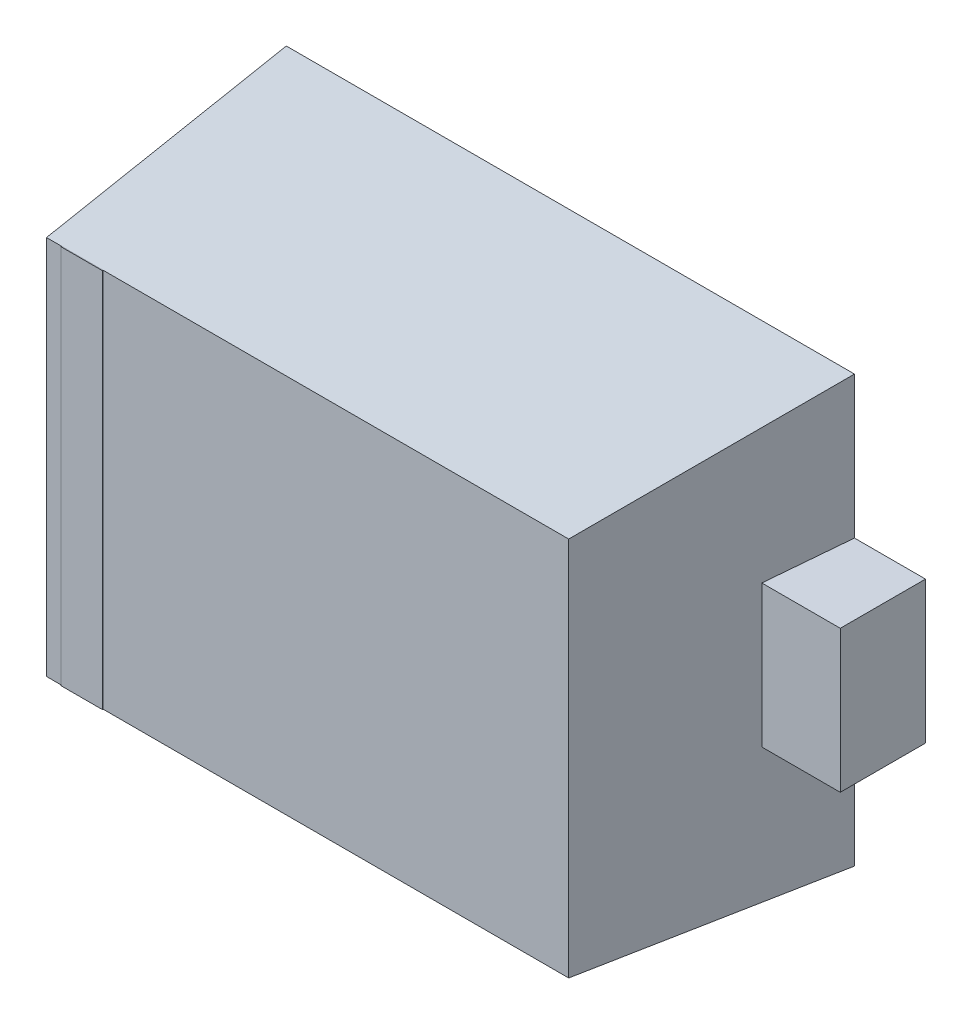
SolidWorks part; units mm, degrees
ref_plane "Front Plane" through (0, 0, 0) normal (0, 0, 1) x (1, 0, 0)
ref_plane "Top Plane" through (0, 0, 0) normal (0, 1, 0) x (1, 0, 0)
ref_plane "Right Plane" through (0, 0, 0) normal (1, 0, 0) x (0, 0, -1)
sketch "Sketch1" plane through (0, 0, 0) normal (0, 0, 1) x (1, 0, 0)
  line L1 (-0.4, -0.3) -> (0.4, -0.3)
  line L2 (-0.4, -0.3) -> (-0.4, 0.3)
  line L3 (-0.4, 0.3) -> (0.4, 0.3)
  line L4 (0.4, -0.3) -> (0.4, 0.3)
  line L5 (-0.4, -0.3) -> (0.4, 0.3) construction
  line L6 (-0.4, 0.3) -> (0.4, -0.3) construction
  point P0 (0, 0)
  dimension "D1" = 0.8
  dimension "D2" = 0.6
extrude "Boss-Extrude1" add sketch "Sketch1" along normal blind 0.37 draft 5
sketch "Sketch2" plane through (0, 0, 0) normal (0, 0, -1) x (-1, 0, 0)
  line L0 (0, 0) -> (0.405, 0) construction
  line L1 (0, 0) -> (0, 0.4925) construction
  line L2 (0.5, -0.1) -> (0.31, -0.1)
  line L3 (0.5, -0.1) -> (0.5, 0.1)
  line L4 (0.5, 0.1) -> (0.31, 0.1)
  line L5 (0.31, -0.1) -> (0.31, 0.1)
  line L6 (0.5, -0.1) -> (0.31, 0.1) construction
  line L7 (0.5, 0.1) -> (0.31, -0.1) construction
  line L8 (-0.5, 0.1) -> (-0.31, 0.1)
  line L9 (-0.31, -0.1) -> (-0.31, 0.1)
  line L10 (-0.5, -0.1) -> (-0.5, 0.1)
  line L11 (-0.5, -0.1) -> (-0.31, -0.1)
  dimension "D1" = 0.19
  dimension "D2" = 0.2
  dimension "D3" = 0.5
extrude "Boss-Extrude2" add sketch "Sketch2" against normal blind 0.12 separate body
sketch "Sketch3" plane through (0, 0, 0.37) normal (0, 0, 1) x (1, 0, 0)
  line L0 (0.3676, 0.2676) -> (-0.3676, 0.2676) construction
  line L1 (-0.3461, 0.2676) -> (-0.2878, 0.2676)
  line L2 (-0.3461, 0.2676) -> (-0.3461, -0.2676)
  line L3 (-0.3461, -0.2676) -> (-0.2878, -0.2676)
  line L4 (-0.2878, 0.2676) -> (-0.2878, -0.2676)
  line L5 (-0.3676, -0.2676) -> (0.3676, -0.2676) construction
extrude "Boss-Extrude3" add sketch "Sketch3" along normal blind 0.001
